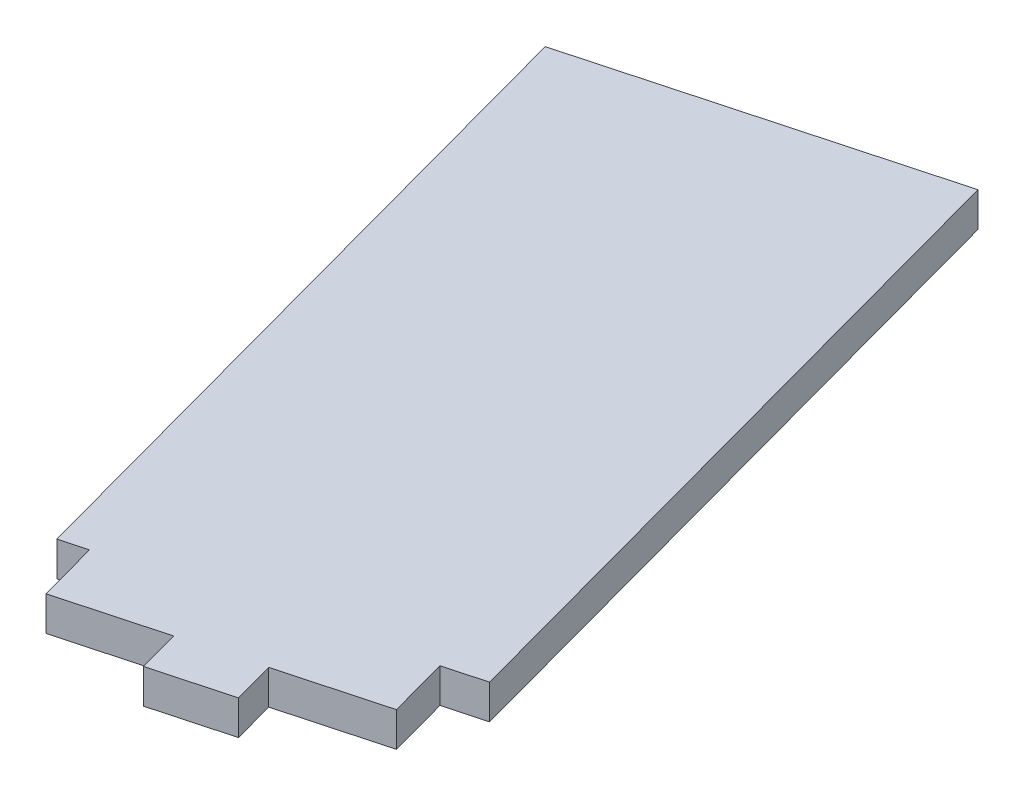
SolidWorks part; units mm, degrees
ref_plane "Plan de face" through (0, 0, 0) normal (0, 0, 1) x (1, 0, 0)
ref_plane "Plan de dessus" through (0, 0, 0) normal (0, 1, 0) x (1, 0, 0)
ref_plane "Plan de droite" through (0, 0, 0) normal (1, 0, 0) x (0, 0, -1)
sketch "Esquisse1" plane through (0, 0, 0) normal (0, 1, 0) x (1, 0, 0)
  line L0 (-12.462, 31.963) -> (12.6618, 38.7904)
  line L11 (0.993, -17.5493) -> (-12.462, 31.963)
  line L13 (0.993, -17.5493) -> (2.8926, -17.0331)
  line L14 (2.8926, -17.0331) -> (4.0915, -21.4451)
  line L17 (4.0915, -21.4451) -> (11.5061, -19.4302)
  line L18 (11.5061, -19.4302) -> (12.3387, -22.4941)
  line L19 (12.3387, -22.4941) -> (17.8537, -20.9954)
  line L20 (-10.0961, 30.7635) -> (2.9925, -17.4008) construction
  line L21 (12.6618, 38.7904) -> (26.1168, -10.7219)
  line L29 (17.8537, -20.9954) -> (17.0211, -17.9315)
  line L30 (17.0211, -17.9315) -> (24.4357, -15.9166)
  line L31 (10.248, 36.292) -> (-10.0961, 30.7635) construction
  line L32 (24.4357, -15.9166) -> (23.2368, -11.5046)
  line L33 (23.2368, -11.5046) -> (26.1168, -10.7219)
  line L39 (2.5062, -13.1899) -> (4.2047, -19.4403) construction
  line L40 (21.6248, -7.9944) -> (23.3234, -14.2448) construction
  line L43 (2.4312, 26.7979) -> (0.7327, 33.0482) construction
  point P7 (24.4414, -15.9166)
  point P8 (3.7657, -20.5303)
  point P10 (0, 0)
  point P11 (4.0972, -21.4451)
  point P21 (23.6249, -13.1648)
  point P32 (0, 0)
  point P33 (1.6094, -15.3909)
  point P34 (0, 0)
  point P39 (0.0999, 35.3767)
  dimension "D1" = 26.035
  dimension "D2" = 51.308
  dimension "D3" = 4.572
  dimension "D4" = 3.175
  dimension "D5" = 5.715
  dimension "D6" = 7.6835
  dimension "D7" = 4.572
extrude "Boss.-Extru.1" add sketch "Esquisse1" along normal blind 2.54
